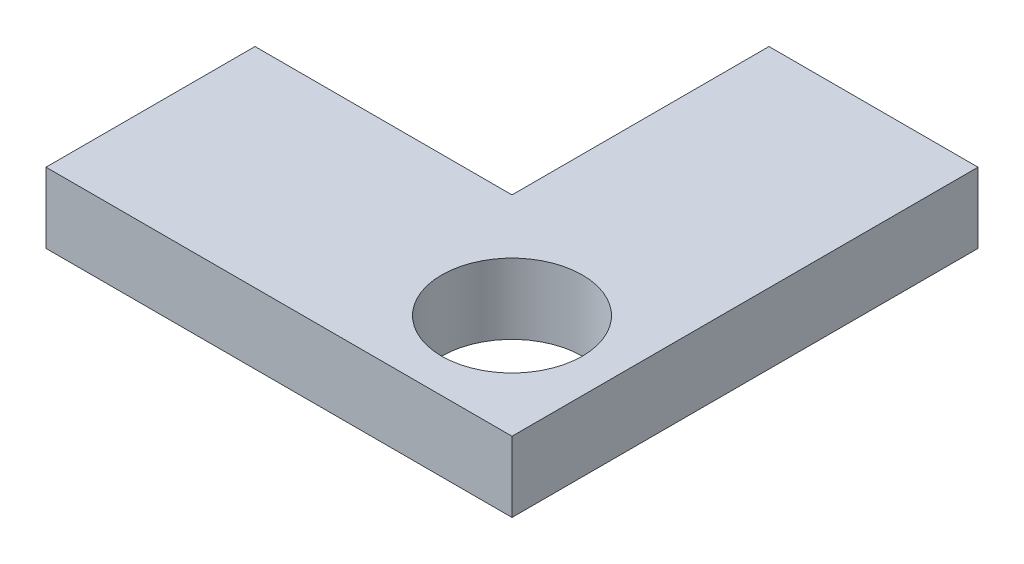
SolidWorks part; units mm, degrees
ref_plane "Front Plane" through (0, 0, 0) normal (0, 0, 1) x (1, 0, 0)
ref_plane "Top Plane" through (0, 0, 0) normal (0, 1, 0) x (1, 0, 0)
ref_plane "Right Plane" through (0, 0, 0) normal (1, 0, 0) x (0, 0, -1)
sketch "Sketch1" plane through (0, 0, 0) normal (0, 1, 0) x (1, 0, 0)
  line L0 (0, 25.6823) -> (0, 0) construction
  line L1 (0, 0) -> (-25.6823, 0) construction
  line L8 (-25.6823, 7.4244) -> (-7.4244, 7.4244)
  line L9 (-7.4244, 7.4244) -> (-7.4244, 25.6823)
  line L10 (-7.4244, 25.6823) -> (7.4244, 25.6823)
  line L11 (7.4244, 25.6823) -> (7.4244, -7.4244)
  line L12 (7.4244, -7.4244) -> (-25.6823, -7.4244)
  line L13 (-25.6823, -7.4244) -> (-25.6823, 7.4244)
  circle A1 centre (0, 0) radius 5
  point P2 (-23.9655, -7.8111)
  point P10 (0, 0)
  point P12 (-25.6823, 0)
  point P13 (0, 0)
  point P14 (0, 25.6823)
  point P15 (19.0576, 2.1147)
  point P16 (-1.7805, 6.645)
  point P17 (-1.9894, 7.4244)
  dimension "D1" = 10
  dimension "D2" = 90
extrude "Boss-Extrude1" add sketch "Sketch1" along normal blind 5
sketch "Sketch2" plane through (0, 5, 0) normal (0, 1, 0) x (1, 0, 0)
  line L2 (-25.6823, 7.4244) -> (-25.6823, -7.4244) construction
  line L3 (-25.6823, -7.4244) -> (7.4244, -7.4244) construction
  point P0 (-18.1823, 0.0756)
  point P1 (-18.1823, 0)
  point P5 (0, 0)
  dimension "D1" = 7.5
  dimension "D2" = 7.5
